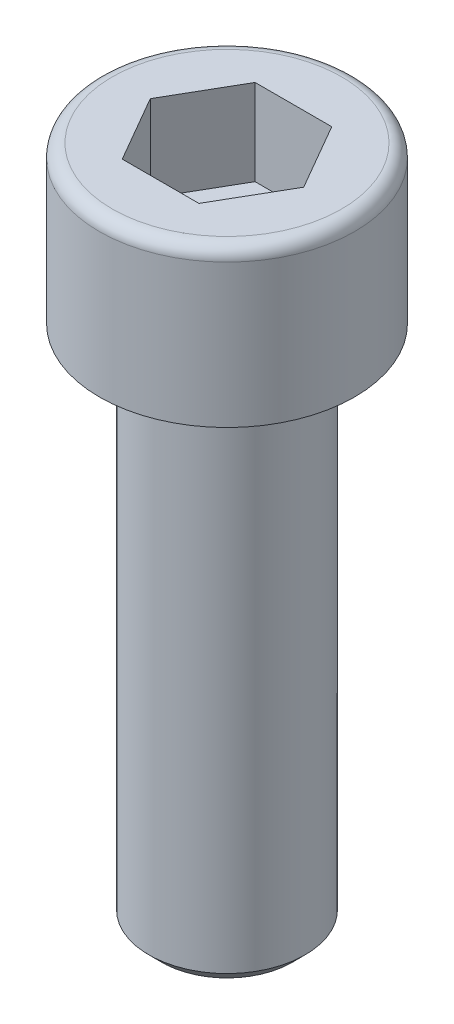
SolidWorks part; units mm, degrees
ref_plane "Plan de face" through (0, 0, 0) normal (0, 0, 1) x (1, 0, 0)
ref_plane "Plan de dessus" through (0, 0, 0) normal (0, 1, 0) x (1, 0, 0)
ref_plane "Plan de droite" through (0, 0, 0) normal (1, 0, 0) x (0, 0, -1)
sketch "Esquisse1" plane through (0, 0, 0) normal (0, 0, 1) x (1, 0, 0)
  line L0 (4.9, 6) -> (0, 6)
  line L1 (0, 6) -> (0, 0)
  line L2 (0, 0) -> (4.9, 0)
  line L3 (4.9, 0) -> (4.9, 6)
  line L4 (0, 6) -> (0, 0) construction
revolve "Révolution1" add sketch "Esquisse1" angle 360 about L4
sketch "Esquisse2" plane through (0, 0, 0) normal (0, -1, 0) x (1, 0, 0)
  circle A0 centre (0, 0) radius 3
extrude "Boss.-Extru.1" add sketch "Esquisse2" along normal blind 20
sketch "Esquisse3" plane through (0, 6, 0) normal (0, 1, 0) x (-1, 0, 0)
  line L0 (1.4722, 2.55) -> (-1.4722, 2.55)
  line L1 (-1.4722, 2.55) -> (-2.9445, 0)
  line L2 (-2.9445, 0) -> (-1.4722, -2.55)
  line L3 (-1.4722, -2.55) -> (1.4722, -2.55)
  line L4 (1.4722, -2.55) -> (2.9445, 0)
  line L5 (2.9445, 0) -> (1.4722, 2.55)
extrude "Enlèv. mat.-Extru.1" cut sketch "Esquisse3" against normal blind 3.3
chamfer "Chanfrein1" distance 0.5 angle 45 1 edges at (0, -20, -3)
fillet "Congé1" radius 0.5 1 edges at (0, 6, -4.9)
